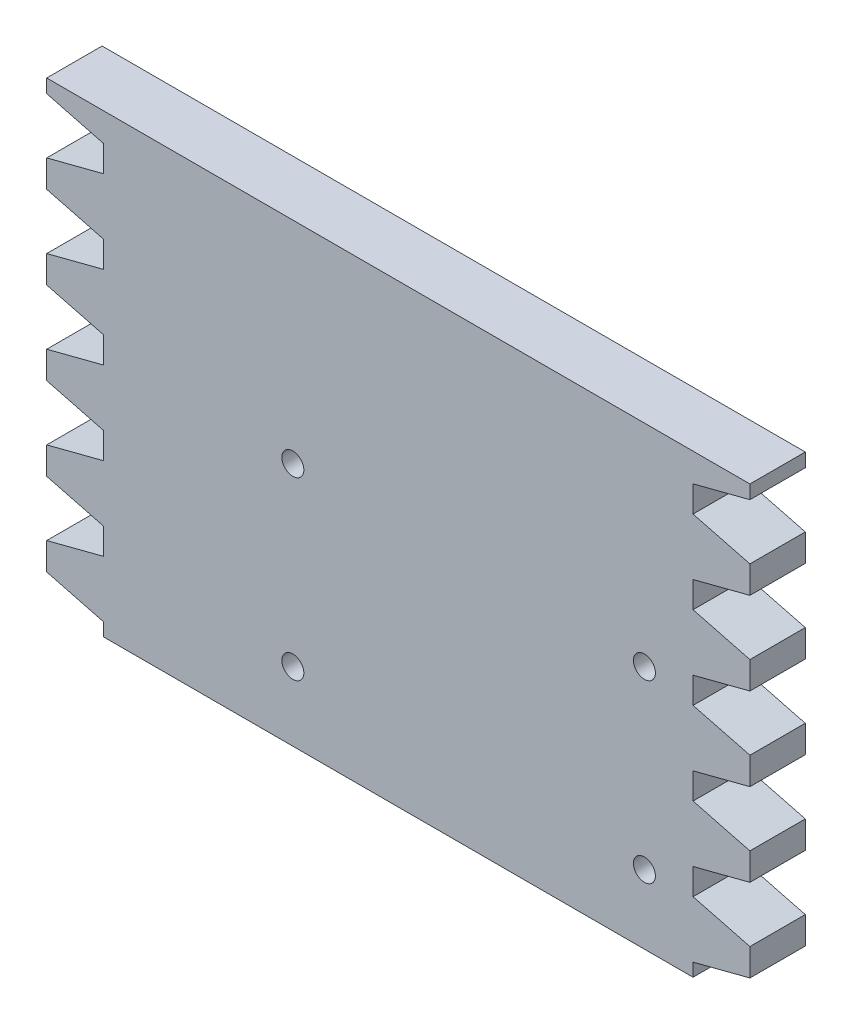
SolidWorks part; units mm, degrees
ref_plane "Front Plane" through (0, 0, 0) normal (0, 0, 1) x (1, 0, 0)
ref_plane "Top Plane" through (0, 0, 0) normal (0, 1, 0) x (1, 0, 0)
ref_plane "Right Plane" through (0, 0, 0) normal (1, 0, 0) x (0, 0, -1)
sketch "Sketch1" plane through (0, 0, 0) normal (0, 0, 1) x (1, 0, 0)
  line L0 (-19.05, 32.9161) -> (31.75, 32.9161)
  line L1 (31.75, 31.9317) -> (31.75, 32.9161)
  line L2 (27.6409, 30.869) -> (31.75, 31.9317)
  line L3 (6.35, 32.9161) -> (6.35, 0) construction
  line L4 (27.6409, 0) -> (-14.9409, 0)
  line L5 (-14.9409, 0) -> (-14.9409, 0.9453)
  line L6 (-14.9409, 0.9453) -> (-19.05, 2.008)
  line L7 (27.6409, 28.9784) -> (27.6409, 30.869)
  line L8 (-19.05, 2.008) -> (-19.05, 3.9768)
  line L9 (-19.05, 3.9768) -> (-14.9409, 5.0394)
  line L10 (-14.9409, 5.0394) -> (-14.9409, 6.9301)
  line L11 (-14.9409, 6.9301) -> (-19.05, 7.9927)
  line L12 (-19.05, 7.9927) -> (-19.05, 9.9615)
  line L13 (-19.05, 9.9615) -> (-14.9409, 11.0242)
  line L14 (-14.9409, 11.0242) -> (-14.9409, 12.9148)
  line L15 (-14.9409, 12.9148) -> (-19.05, 13.9775)
  line L16 (-19.05, 13.9775) -> (-19.05, 15.9463)
  line L17 (-19.05, 15.9463) -> (-14.9409, 17.0089)
  line L18 (-14.9409, 17.0089) -> (-14.9409, 18.8996)
  line L19 (31.75, 27.9158) -> (27.6409, 28.9784)
  line L20 (31.75, 25.947) -> (31.75, 27.9158)
  line L21 (-14.9409, 18.8996) -> (-19.05, 19.9622)
  line L22 (-19.05, 19.9622) -> (-19.05, 21.931)
  line L23 (-19.05, 21.931) -> (-14.9409, 22.9937)
  line L24 (-14.9409, 22.9937) -> (-14.9409, 24.8843)
  line L25 (-14.9409, 24.8843) -> (-19.05, 25.947)
  line L26 (-19.05, 25.947) -> (-19.05, 27.9158)
  line L27 (-19.05, 27.9158) -> (-14.9409, 28.9784)
  line L28 (-14.9409, 28.9784) -> (-14.9409, 30.869)
  line L29 (-14.9409, 30.869) -> (-19.05, 31.9317)
  line L30 (-19.05, 31.9317) -> (-19.05, 32.9161)
  line L31 (27.6409, 24.8843) -> (31.75, 25.947)
  line L32 (27.6409, 22.9937) -> (27.6409, 24.8843)
  line L33 (31.75, 21.931) -> (27.6409, 22.9937)
  line L34 (31.75, 19.9622) -> (31.75, 21.931)
  line L35 (27.6409, 18.8996) -> (31.75, 19.9622)
  line L36 (27.6409, 17.0089) -> (27.6409, 18.8996)
  line L37 (31.75, 15.9463) -> (27.6409, 17.0089)
  line L38 (31.75, 13.9775) -> (31.75, 15.9463)
  line L39 (27.6409, 12.9148) -> (31.75, 13.9775)
  line L40 (27.6409, 11.0242) -> (27.6409, 12.9148)
  line L41 (31.75, 9.9615) -> (27.6409, 11.0242)
  line L42 (31.75, 7.9927) -> (31.75, 9.9615)
  line L43 (27.6409, 6.9301) -> (31.75, 7.9927)
  line L44 (27.6409, 5.0394) -> (27.6409, 6.9301)
  line L45 (31.75, 3.9768) -> (27.6409, 5.0394)
  line L46 (31.75, 2.008) -> (31.75, 3.9768)
  line L47 (27.6409, 0.9453) -> (31.75, 2.008)
  line L48 (27.6409, 0) -> (27.6409, 0.9453)
  dimension "D1" = 25.4
  dimension "D2" = 32.9161
extrude "Boss-Extrude1" add sketch "Sketch1" along normal blind 4 contours L0 L1 L2 L7 L19 L20 L31 L32 L33 L34 L35 L36 L37 L38 L39 L40 L41 L42 L43 L44 L45 L46 L47 L48 L4 L5 L6 L8 L9 L10 L11 L12 L13 L14 L15 L16 L17 L18 L21 L22 L23 L24 L25 L26 L27 L28 L29 L30
sketch "Sketch2" plane through (0, 0, 4) normal (0, 0, 1) x (1, 0, 0)
  line L0 (-19.05, 32.9161) -> (31.75, 32.9161) construction
  circle A0 centre (-1.27, 17.6761) radius 0.7937
  circle A1 centre (24.13, 17.6761) radius 0.7937
  circle A2 centre (24.13, 4.9761) radius 0.7937
  circle A3 centre (-1.27, 4.9761) radius 0.7938
  point P4 (6.35, 32.9161)
  dimension "D3" = 1.5875
  dimension "D1" = 15.24
  dimension "D2" = 7.62
  dimension "D6" = 12.7
  dimension "D4" = 2
  dimension "D5" = 2
extrude "Cut-Extrude1" cut sketch "Sketch2" against normal blind 4
